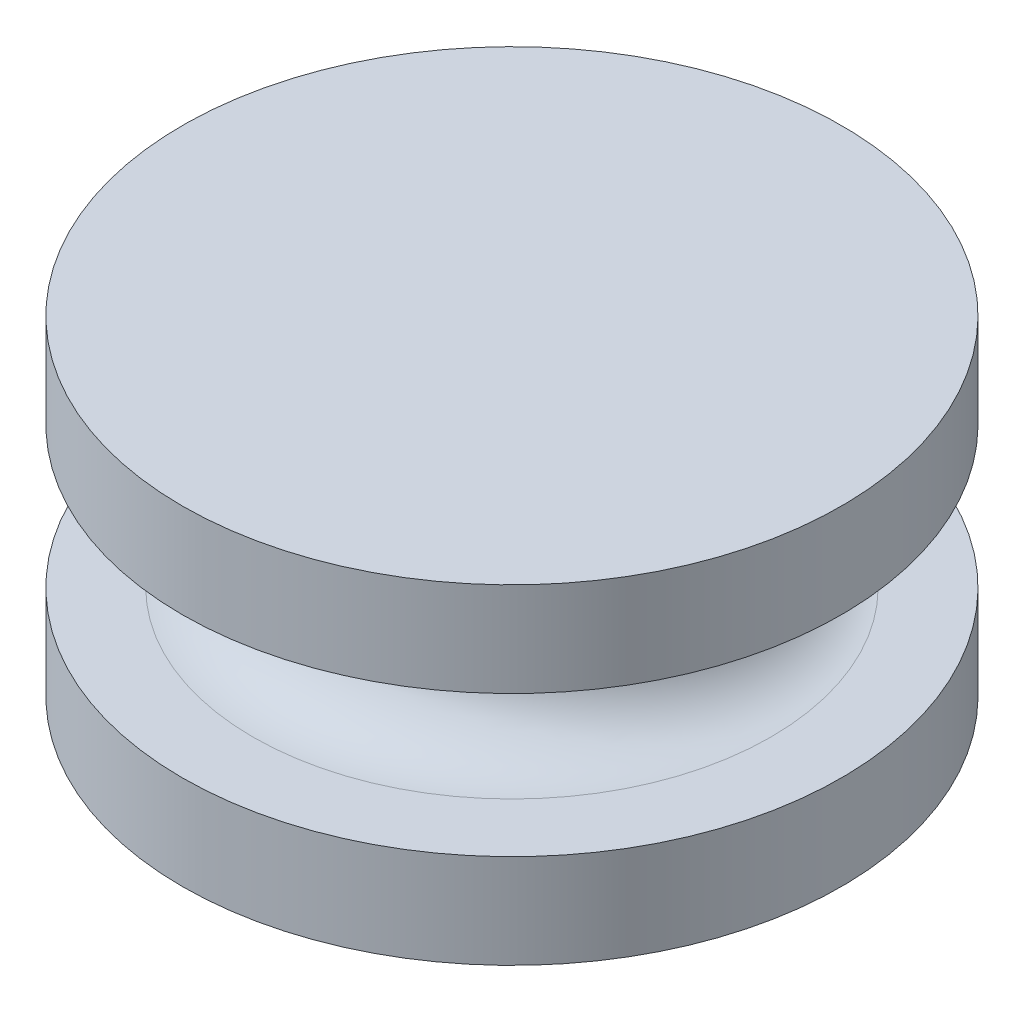
SolidWorks part; units mm, degrees
material "ABS"
ref_plane "正面" through (0, 0, 0) normal (0, 0, 1) x (1, 0, 0)
ref_plane "平面" through (0, 0, 0) normal (0, 1, 0) x (1, 0, 0)
ref_plane "右側面" through (0, 0, 0) normal (1, 0, 0) x (0, 0, -1)
sketch "ｽｹｯﾁ1" plane through (0, 0, 0) normal (0, 0, 1) x (1, 0, 0)
  line L0 (0, 0) -> (0, 6) construction
  line L1 (0, 3.5) -> (-7, 3.5)
  line L2 (-7, 3.5) -> (-7, 1.5)
  line L3 (-7, 1.5) -> (-5.5, 1.5)
  line L4 (-4, 0) -> (0, 0) construction
  line L5 (-7, -3.5) -> (-7, -1.5)
  line L6 (-7, -1.5) -> (-5.5, -1.5)
  line L7 (0, -3.5) -> (-7, -3.5)
  line L8 (0, 3.5) -> (0, -3.5)
  arc A0 (-5.5, 1.5) -> (-5.5, -1.5) centre (-5.5, 0) cw
  dimension "D1" = 3.5
  dimension "D2" = 1.5
  dimension "D3" = 4
  dimension "D4" = 7
revolve "回転1" add sketch "ｽｹｯﾁ1" angle 360 about L8
